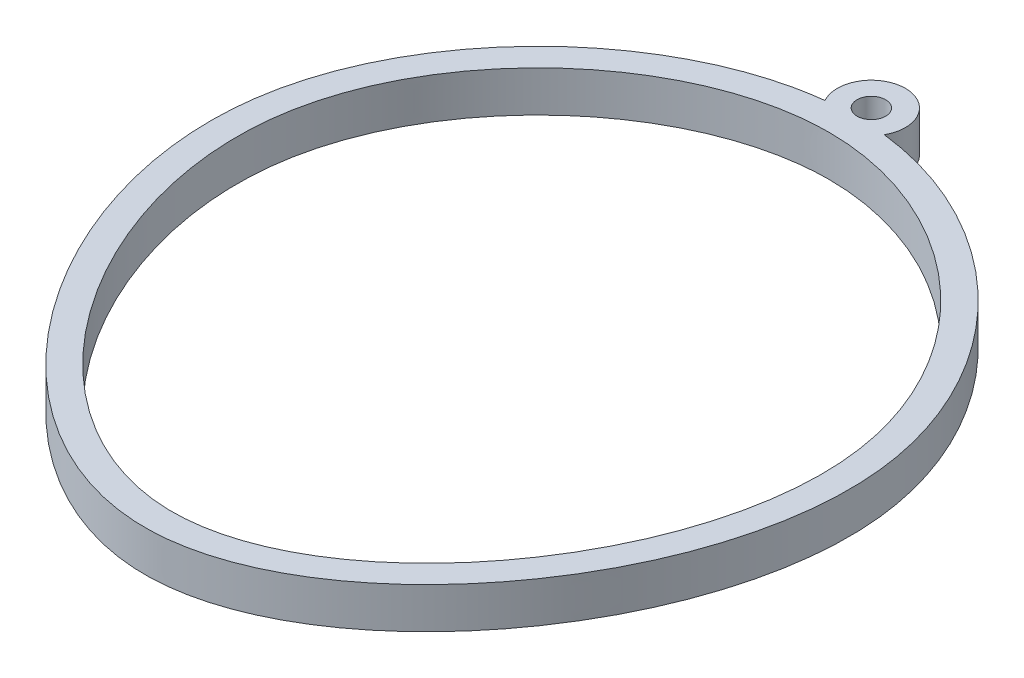
SolidWorks part; units mm, degrees
ref_plane "Front Plane" through (0, 0, 0) normal (0, 0, 1) x (1, 0, 0)
ref_plane "Top Plane" through (0, 0, 0) normal (0, 1, 0) x (1, 0, 0)
ref_plane "Right Plane" through (0, 0, 0) normal (1, 0, 0) x (0, 0, -1)
sketch "Sketch1" plane through (0, 0, 0) normal (0, 1, 0) x (1, 0, 0)
  line L0 (0, 19.143) -> (0, -29.113) construction
  line L1 (-21.27, 0) -> (21.27, 0) construction
  line L2 (0, 21.143) -> (0, -31.113) construction
  line L3 (-23.27, 0) -> (23.27, 0) construction
  circle A0 centre (0, 22.243) radius 1.05
  arc A1 (2.1783, 21.0162) -> (-2.1783, 21.0162) centre (0, 22.243) ccw
  spline S0 degree 3 poles (-32.2853, -0.5068) (0, 27.8377) (32.2853, -0.5068) (0, -45.0614) (-32.2853, -0.5068) (0, 27.8377) (32.2853, -0.5068) knots -0.778758 -0.5 -0.221242 0 0.221242 0.5 0.778758 1 1.221242 1.5 1.778758 only from (0, 19.143) to (0, 19.143)
  spline S1 degree 3 poles (-35.2538, -0.4747) (0, 30.8122) (35.2538, -0.4747) (0, -48.0474) (-35.2538, -0.4747) (0, 30.8122) (35.2538, -0.4747) knots -0.77636 -0.5 -0.22364 0 0.22364 0.5 0.77636 1 1.22364 1.5 1.77636 only from (0, 21.143) to (0, 21.143)
  dimension "D9" = 5
  dimension "D10" = 2.1
  dimension "D1" = 48.256
  dimension "D2" = 42.54
  dimension "D3" = 19.143
  dimension "D4" = 21.27
  dimension "D5" = 52.256
  dimension "D6" = 2
  dimension "D7" = 46.54
  dimension "D8" = 2
  dimension "D11" = 3.1
extrude "Boss-Extrude1" add sketch "Sketch1" along normal blind 3 contours A1 S1 A0 | S1 S0
